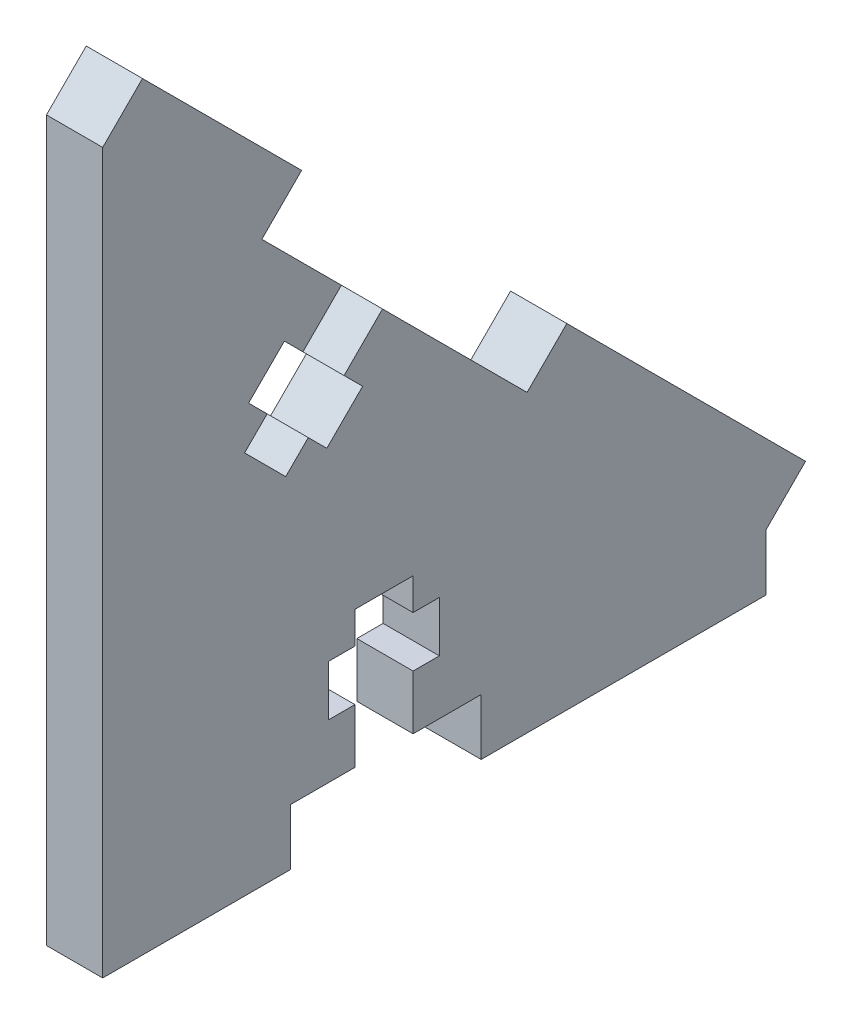
SolidWorks part; units mm, degrees
ref_plane "Front Plane" through (0, 0, 0) normal (0, 0, 1) x (1, 0, 0)
ref_plane "Top Plane" through (0, 0, 0) normal (0, 1, 0) x (1, 0, 0)
ref_plane "Right Plane" through (0, 0, 0) normal (1, 0, 0) x (0, 0, -1)
sketch "Sketch2" plane through (0, 0, 0) normal (1, 0, 0) x (0, 0, -1)
  line L0 (0, 0) -> (0, 35.3553)
  line L1 (0, 35.3553) -> (35.3553, 0)
  line L2 (35.3553, 0) -> (0, 0)
  dimension "D1" = 45
  dimension "D2" = 50
extrude "Boss-Extrude1" add sketch "Sketch2" along normal blind 3
sketch "Sketch4" plane through (0, 0, 0) normal (0, -1, 0) x (1, 0, 0)
  line L0 (0, 0) -> (0, -35.3553) construction
  line L1 (0, -10) -> (3, -10)
  line L3 (0, -20.18) -> (3, -20.18)
  line L5 (3, 0) -> (3, -35.3553) construction
  line L6 (3, 0) -> (0, 0) construction
  line L7 (3, -10) -> (3, 0)
  line L8 (3, 0) -> (0, 0)
  line L9 (0, 0) -> (0, -10)
  line L10 (3, -20.18) -> (3, -35.3553)
  line L11 (3, -35.3553) -> (0, -35.3553)
  line L12 (0, -35.3553) -> (0, -20.18)
  dimension "D1" = 3
  dimension "D2" = 10.18
  dimension "D3" = 10
extrude "Boss-Extrude3" add sketch "Sketch4" along normal blind 3
sketch "Sketch5" plane through (3, 0, 0) normal (1, 0, 0) x (0, 0, -1)
  line L0 (13.45, 0) -> (13.45, 2.9)
  line L1 (13.45, 2.9) -> (12.05, 2.9)
  line L2 (12.05, 2.9) -> (12.05, 5.6)
  line L3 (12.05, 5.6) -> (13.45, 5.6)
  line L4 (13.45, 5.6) -> (13.45, 7.3)
  line L5 (13.45, 7.3) -> (16.55, 7.3)
  line L6 (16.55, 7.3) -> (16.55, 5.6)
  line L7 (16.55, 5.6) -> (17.95, 5.6)
  line L8 (17.95, 5.6) -> (17.95, 2.9)
  line L9 (17.95, 2.9) -> (16.55, 2.9)
  line L10 (16.55, 2.9) -> (16.55, 0)
  line L11 (16.55, 0) -> (13.45, 0)
  line L12 (10, 0) -> (20.18, 0) construction
  line L13 (10, -3) -> (10, 0) construction
  dimension "D1" = 3.1
  dimension "D2" = 1.4
  dimension "D3" = 1.7
  dimension "D4" = 2.7
  dimension "D5" = 2.9
  dimension "D6" = 0
  dimension "D7" = 3.45
extrude "Cut-Extrude1" cut sketch "Sketch5" against normal blind 10
sketch "Sketch6" plane through (0, 17.6777, -17.6777) normal (0, 0.7071, -0.7071) x (1, 0, 0)
  line L0 (0, 25) -> (0, -25) construction
  line L1 (3, -25) -> (0, -25)
  line L2 (3, -25) -> (3, -13)
  line L3 (3, -13) -> (0, -13)
  line L4 (0, -25) -> (0, -13)
  line L6 (3, 25) -> (0, 25)
  line L7 (3, 25) -> (3, 7)
  line L8 (3, 7) -> (0, 7)
  line L9 (0, 25) -> (0, 7)
  dimension "D1" = 12
  dimension "D2" = 18
extrude "Boss-Extrude4" add sketch "Sketch6" along normal blind 3
sketch "Sketch7" plane through (3, 0, 0) normal (1, 0, 0) x (0, 0, -1)
  line L13 (22.6274, 12.7279) -> (8.4853, 26.8701) construction
  line L14 (10.6066, 28.9914) -> (8.4853, 26.8701) construction
  line B0 (14.92, 20.4354) -> (12.8693, 18.3848)
  line B1 (12.8693, 18.3848) -> (13.8593, 17.3948)
  line B2 (13.8593, 17.3948) -> (11.9501, 15.4856)
  line B3 (11.9501, 15.4856) -> (10.9602, 16.4756)
  line B4 (10.9602, 16.4756) -> (9.7581, 15.2735)
  line B5 (9.7581, 15.2735) -> (7.566, 17.4655)
  line B6 (7.566, 17.4655) -> (8.7681, 18.6676)
  line B7 (8.7681, 18.6676) -> (7.7782, 19.6576)
  line B8 (7.7782, 19.6576) -> (9.6874, 21.5668)
  line B9 (9.6874, 21.5668) -> (10.6773, 20.5768)
  line B10 (10.6773, 20.5768) -> (12.7279, 22.6274)
  line B11 (12.7279, 22.6274) -> (14.92, 20.4354)
  dimension "D1" = 0
  dimension "D2" = 6
sketch_block_instance "Block1-1"
sketch_block "Block1" parameters "D1"=3.1, "D2"=1.4, "D3"=1.7, "D4"=2.7, "D5"=2.9
extrude "Cut-Extrude2" cut sketch "Sketch7" against normal blind 3
equation "\"Servo_Angle\"=45"
equation "\"Big_Teeth\"= 24"
equation "\"Small_Teeth\"= 12"
equation "\"Kerf\"= 0.18mm"
